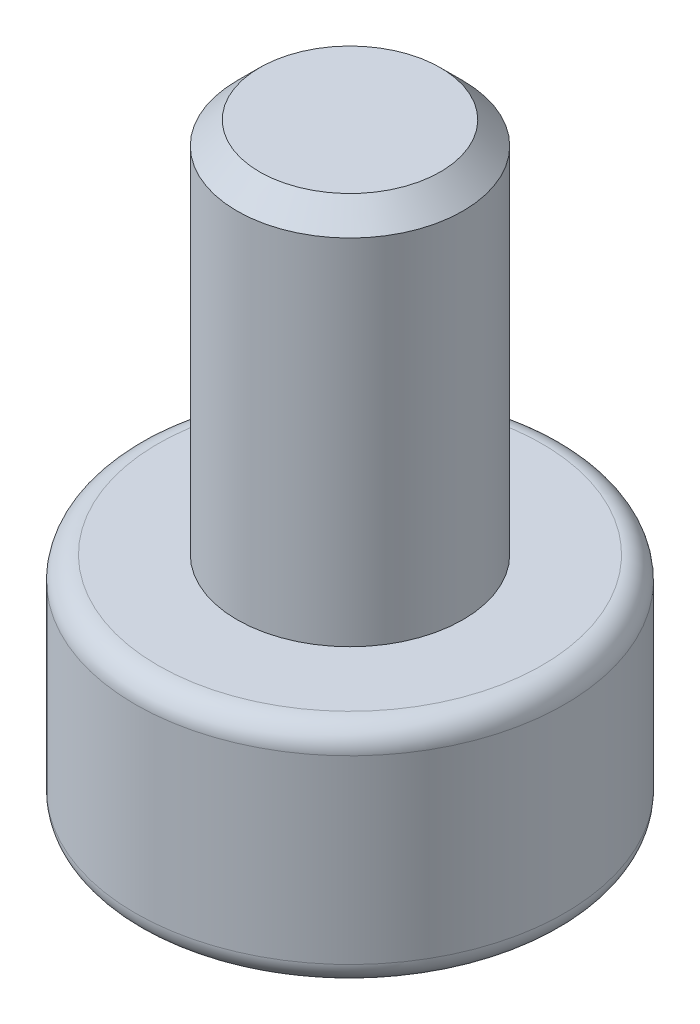
SolidWorks part; units mm, degrees
material "AISI 304"
ref_plane "前视基准面" through (0, 0, 0) normal (0, 0, 1) x (1, 0, 0)
ref_plane "上视基准面" through (0, 0, 0) normal (0, 1, 0) x (1, 0, 0)
ref_plane "右视基准面" through (0, 0, 0) normal (1, 0, 0) x (0, 0, -1)
sketch "草图1" plane through (0, 0, 0) normal (0, 1, 0) x (1, 0, 0)
  circle A0 centre (0, 0) radius 2.85
  dimension "D1" = 5.7
extrude "凸台-拉伸1" add sketch "草图1" along normal blind 3
sketch "草图2" plane through (0, 3, 0) normal (0, 1, 0) x (1, 0, 0)
  circle A0 centre (0, 0) radius 1.5
  dimension "D1" = 3
extrude "凸台-拉伸2" add sketch "草图2" along normal blind 5
sketch "草图3" plane through (0, 0, 0) normal (0, -1, 0) x (1, 0, 0)
  circle A0 centre (0, 0) radius 1.29
  dimension "D1" = 2.58
extrude "切除-拉伸1" cut sketch "草图3" against normal blind 1.3
fillet "圆角1" radius 0.3 2 edges at (0, 3, 2.85) (0, 0, 2.85)
chamfer "倒角1" distance 0.3 angle 45 1 edges at (0, 8, 1.5)
chamfer "倒角2" distance 0.15 angle 45 1 edges at (0, 0, -1.29)
